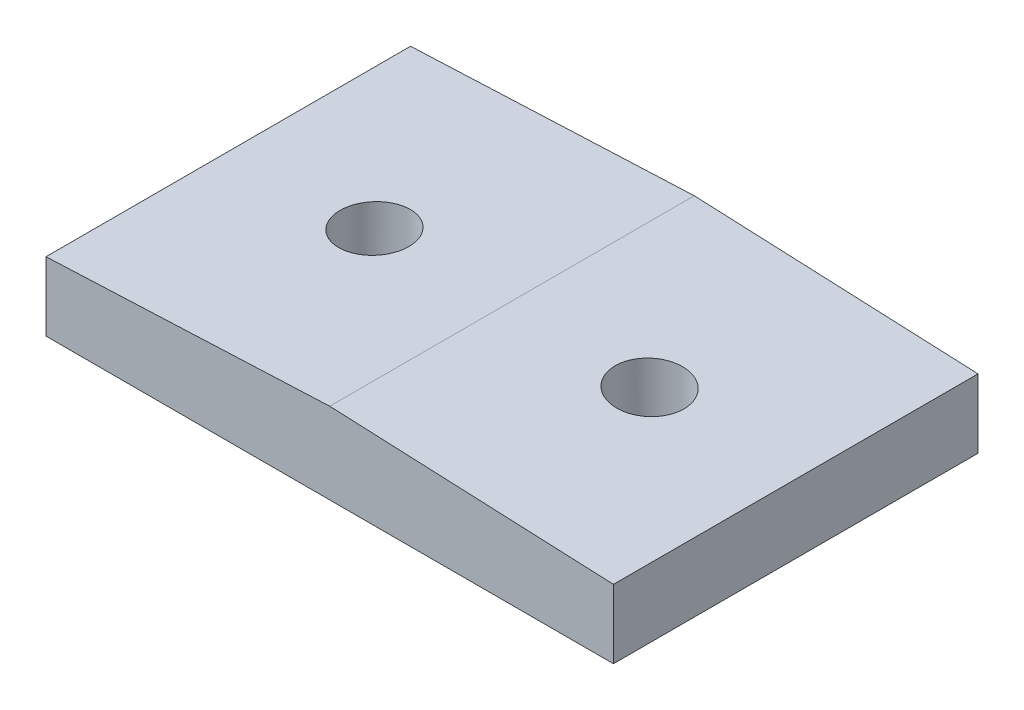
SolidWorks part; units mm, degrees
ref_plane "前视基准面" through (0, 0, 0) normal (0, 0, 1) x (1, 0, 0)
ref_plane "上视基准面" through (0, 0, 0) normal (0, 1, 0) x (1, 0, 0)
ref_plane "右视基准面" through (0, 0, 0) normal (1, 0, 0) x (0, 0, -1)
other "Configuration Table"
sketch "草图1" plane through (0, 0, 0) normal (0, 0, 1) x (1, 0, 0)
  line L0 (-8.25, 0) -> (8.25, 0)
  line L1 (8.25, 0) -> (8.25, 2)
  line L2 (8.25, 2) -> (0, 2.3602)
  line L3 (0, 2.3602) -> (-8.25, 2)
  line L4 (-8.25, 2) -> (-8.25, 0)
  point P6 (0, 0)
  point P8 (0, 0)
  dimension "D1" = 16.5
  dimension "D2" = 2
  dimension "D3" = 175
extrude "凸台-拉伸1" add sketch "草图1" along normal blind 10.6
sketch "草图2" plane through (0, 0, 0) normal (0, -1, 0) x (1, 0, 0)
  line L0 (0, 10.6) -> (0, 0) construction
  line L1 (-8.25, 10.6) -> (8.25, 10.6) construction
  line L2 (0, 5.3) -> (8.25, 5.3) construction
  line L3 (8.25, 10.6) -> (8.25, 0) construction
  circle A0 centre (4, 5.3) radius 1
  circle A1 centre (-4, 5.3) radius 1
  point P11 (0, 0)
  point P12 (0, 0)
  dimension "D1" = 2
  dimension "D2" = 8
extrude "切除-拉伸1" cut sketch "草图2" against normal through all
